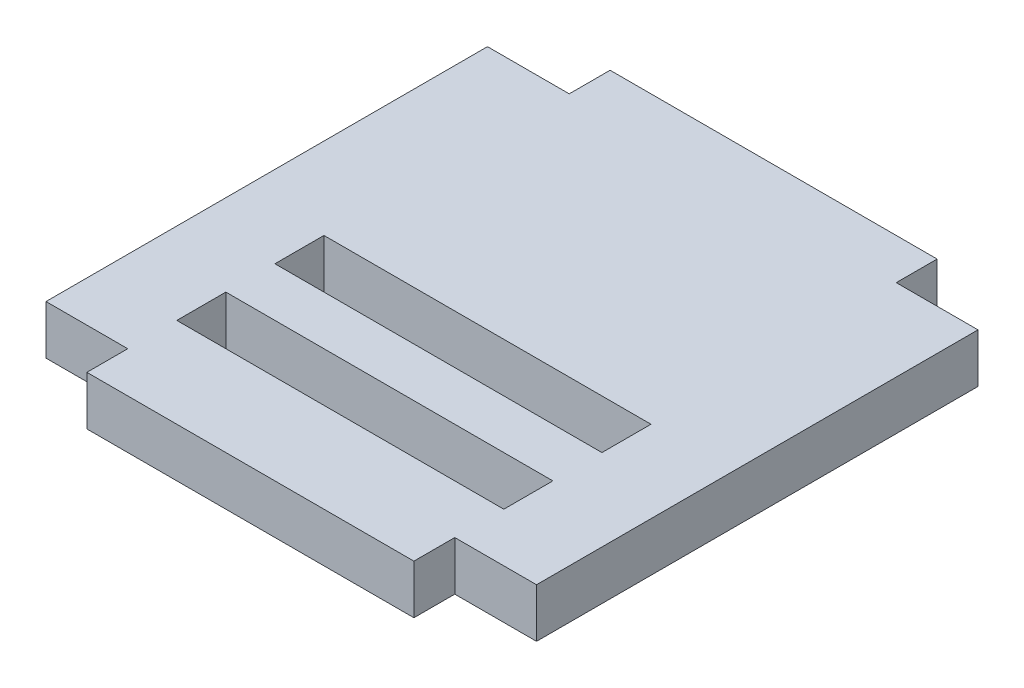
SolidWorks part; units mm, degrees
ref_plane "前视基准面" through (0, 0, 0) normal (0, 0, 1) x (1, 0, 0)
ref_plane "上视基准面" through (0, 0, 0) normal (0, 1, 0) x (1, 0, 0)
ref_plane "右视基准面" through (0, 0, 0) normal (1, 0, 0) x (0, 0, -1)
sketch "草图1" plane through (0, 0, 0) normal (0, 1, 0) x (1, 0, 0)
  line L0 (-23.1429, 0) -> (21.0765, 0) construction
  line L1 (-15, 13.5) -> (15, 13.5)
  line L2 (-15, 13.5) -> (-15, -13.5)
  line L3 (-15, -13.5) -> (15, -13.5)
  line L4 (15, 13.5) -> (15, -13.5)
  line L5 (-15, 13.5) -> (15, -13.5) construction
  line L6 (-15, -13.5) -> (15, 13.5) construction
  line L7 (-10, -16) -> (10, -16)
  line L8 (-10, 13.5) -> (10, 13.5)
  line L9 (-10, 13.5) -> (-10, 16)
  line L10 (-10, 16) -> (10, 16)
  line L11 (10, 13.5) -> (10, 16)
  line L12 (-10, -13.5) -> (10, -13.5)
  line L13 (-10, -13.5) -> (-10, -16)
  line L14 (10, -13.5) -> (10, -16)
  line L15 (0, 13.5) -> (0, -13.5) construction
  point P0 (0, 0)
  dimension "D1" = 27
  dimension "D2" = 30
  dimension "D3" = 2.5
  dimension "D4" = 20
extrude "凸台-拉伸1" add sketch "草图1" along normal blind 3 contours L1 L11 L10 L9 | L4 L1 L2 L3 | L14 L3 L13 L7
sketch "草图2" plane through (0, 3, 0) normal (0, 1, 0) x (1, 0, 0)
  line L0 (15, 13.5) -> (15, -13.5) construction
  line L1 (15, -7.5) -> (-15, -7.5) construction
  line L2 (15, -7.5) -> (15, -4.5) construction
  line L3 (15, -4.5) -> (-15, -4.5) construction
  line L4 (-15, -7.5) -> (-15, -4.5) construction
  line L5 (-15, 13.5) -> (-15, -13.5) construction
  line L6 (10, -13.5) -> (15, -13.5) construction
  line L7 (0, -16) -> (0, 16) construction
  line L8 (-10, -16) -> (10, -16) construction
  line L9 (-10, 16) -> (10, 16) construction
  line L10 (-15, -6) -> (15, -6) construction
  line L11 (-10, -7.5) -> (10, -7.5)
  line L12 (-10, -7.5) -> (-10, -10.5)
  line L13 (-10, -10.5) -> (10, -10.5)
  line L14 (10, -7.5) -> (10, -10.5)
  line L15 (-10, -1.5) -> (10, -1.5)
  line L16 (10, -4.5) -> (10, -1.5)
  line L17 (-10, -4.5) -> (10, -4.5)
  line L18 (-10, -4.5) -> (-10, -1.5)
  point P20 (0, -7.5)
  dimension "D1" = 6
  dimension "D2" = 3
  dimension "D3" = 20
  dimension "D4" = 3
extrude "切除-拉伸1" cut sketch "草图2" against normal through all
